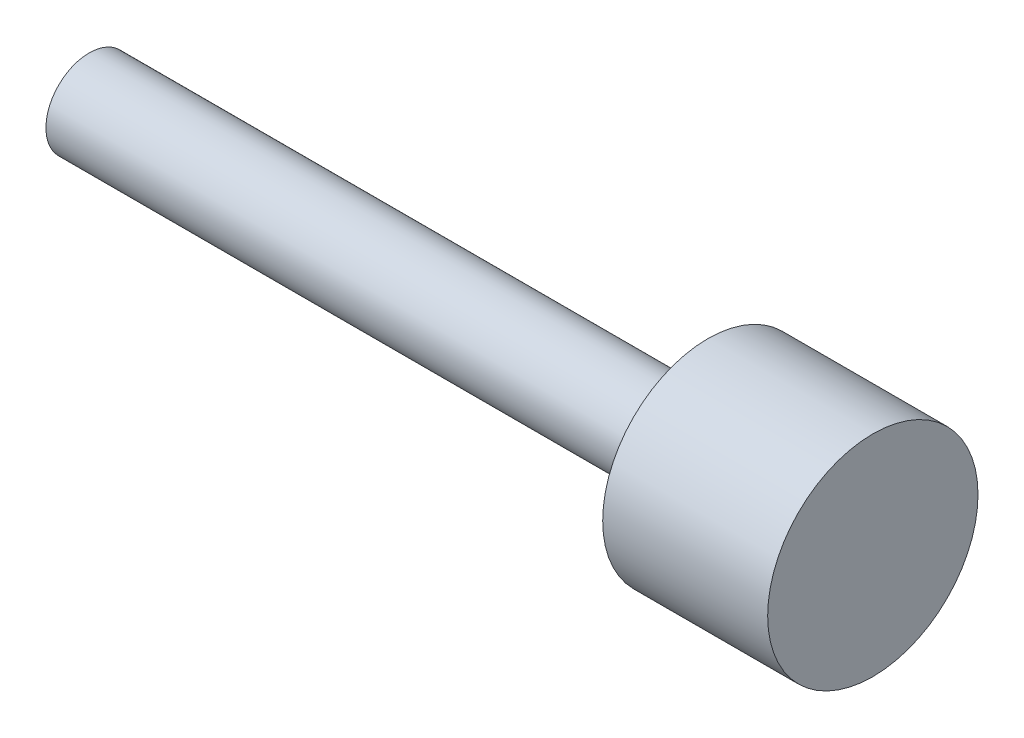
SolidWorks part; units mm, degrees
ref_plane "Front Plane" through (0, 0, 0) normal (0, 0, 1) x (1, 0, 0)
ref_plane "Top Plane" through (0, 0, 0) normal (0, 1, 0) x (1, 0, 0)
ref_plane "Right Plane" through (0, 0, 0) normal (1, 0, 0) x (0, 0, -1)
sketch "Sketch1" plane through (0, 0, 0) normal (0, 0, 1) x (1, 0, 0)
  line L0 (0, 0) -> (0, 2.1)
  line L1 (0, 2.1) -> (30, 2.1)
  line L2 (30, 2.1) -> (30, 5.1)
  line L3 (30, 5.1) -> (33, 5.1)
  line L4 (33, 5.1) -> (33, 0)
  line L5 (33, 0) -> (0, 0)
  dimension "D1" = 5.1
  dimension "D2" = 2.1
  dimension "D3" = 30
  dimension "D4" = 3
revolve "Revolve1" add sketch "Sketch1" angle 360 about L5
ref_plane "Electrode Face USE THIS TO ALIGN" through (33, 0, 0) normal (1, 0, 0) x (0, 0, -1)
sketch "Sketch2" plane through (33, 0, 0) normal (1, 0, 0) x (0, 0, -1)
  circle A1 centre (0, 0) radius 5.1
  circle A2 centre (0, 0) radius 5.1
  dimension "D1" = 0
extrude "Boss-Extrude1" add sketch "Sketch2" along normal blind 5
sketch "Sketch3" plane through (33, 0, 0) normal (1, 0, 0) x (0, 0, -1)
  point P0 (0, 0)
